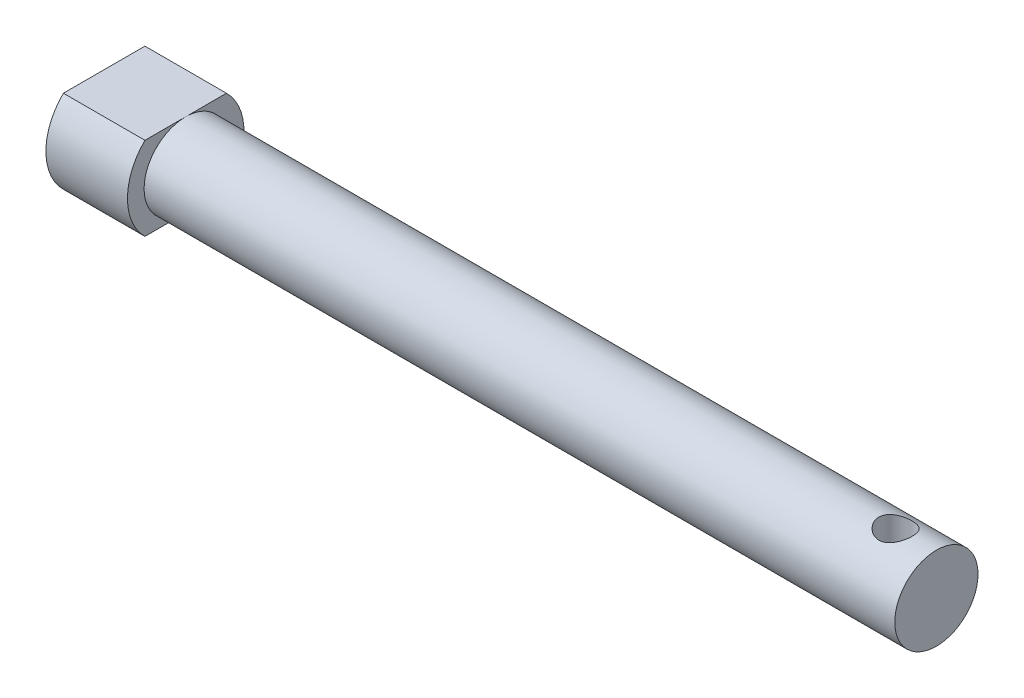
SolidWorks part; units mm, degrees
ref_plane "Front Plane" through (0, 0, 0) normal (0, 0, 1) x (1, 0, 0)
ref_plane "Top Plane" through (0, 0, 0) normal (0, 1, 0) x (1, 0, 0)
ref_plane "Right Plane" through (0, 0, 0) normal (1, 0, 0) x (0, 0, -1)
sketch "Sketch2" plane through (0, 0, 0) normal (1, 0, 0) x (0, 0, -1)
  circle A0 centre (0, 0) radius 2.5
  dimension "D1" = 5
extrude "Boss-Extrude1" add sketch "Sketch2" along normal mid plane 50
sketch "Sketch3" plane through (-25, 0, 0) normal (-1, 0, 0) x (0, 0, 1)
  line L0 (-2.4495, 2.5) -> (2.4495, 2.5)
  line L1 (-2.4495, -2.5) -> (2.4495, -2.5)
  circle A1 centre (0, 0) radius 2.5 construction
  circle A2 centre (0, 0) radius 3.5
  circle A3 centre (0, 0) radius 3.5
  circle M2 centre (0, 0) radius 2.5
  dimension "D1" = 1
extrude "Boss-Extrude4" add sketch "Sketch3" against normal blind 4.9 contours L1 A3 L0 M2 | L0 A3 L1 M2
sketch "Sketch5" plane through (0, 2.5, 0) normal (0, 1, 0) x (1, 0, 0)
  line L0 (-20.1, -2.5) -> (25, -2.5) construction
  line L1 (25, 2.5) -> (20.1, 2.5)
  line L2 (25, 2.5) -> (25, -2.5)
  line L3 (25, -2.5) -> (20.1, -2.5)
  line L4 (20.1, 2.5) -> (20.1, -2.5)
  circle A0 centre (22.55, 0) radius 1
  dimension "D2" = 2
  dimension "D1" = 4.9
  dimension "D3" = 2.45
  dimension "D4" = 2.5
extrude "Cut-Extrude2" cut sketch "Sketch5" against normal through all both and the other way through all contours A0
